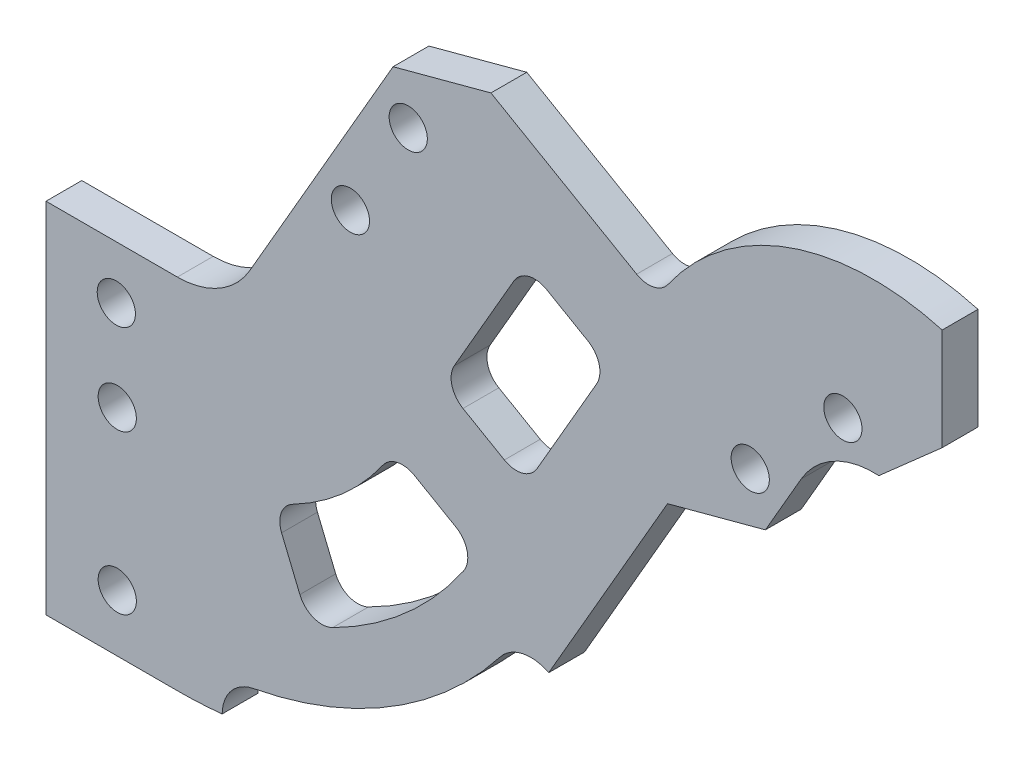
SolidWorks part; units mm, degrees
ref_plane "Front Plane" through (0, 0, 0) normal (0, 0, 1) x (1, 0, 0)
ref_plane "Top Plane" through (0, 0, 0) normal (0, 1, 0) x (1, 0, 0)
ref_plane "Right Plane" through (0, 0, 0) normal (1, 0, 0) x (0, 0, -1)
sketch "Sketch1" plane through (0, 0, 0) normal (0, 0, 1) x (1, 0, 0)
  line L0 (-45.5248, 28.6646) -> (-37.3286, 30.8608) construction
  line L1 (-53.0248, 15.6742) -> (-45.5248, 28.6646) construction
  line L2 (-45.5248, 28.6646) -> (-37.3286, 30.8608)
  line L3 (-57.5248, 7.88) -> (-45.5248, 28.6646)
  line L4 (-30.6183, -5.5166) -> (-22.544, 8.4685) construction
  line L5 (-22.544, 8.4685) -> (-14.3479, 10.6646) construction
  line L6 (-14.3479, 10.6646) -> (-11.3479, 15.8608) construction
  line L7 (-4.8483, 19.3471) -> (0.4544, 24.0249) construction
  line L8 (-32.4942, -8.7657) -> (-22.544, 8.4685)
  line L9 (-22.544, 8.4685) -> (-14.3479, 10.6646)
  line L10 (-14.3479, 10.6646) -> (-11.3479, 15.8608)
  line L11 (-4.8483, 19.3471) -> (0.4544, 24.0249)
  line L12 (0.4544, 24.0249) -> (0.4544, 32.5611)
  line L13 (-63.587, 4.38) -> (-74.587, 4.38)
  line L14 (-74.587, 4.38) -> (-74.587, -25.62)
  line L15 (-74.587, -25.62) -> (-63.587, -25.62)
  line L16 (-63.587, -1.62) -> (-63.587, -25.62) construction
  line L17 (-28.6042, 25.8237) -> (-25.1288, 23.8172) construction
  line L18 (-29.2043, 16.9326) -> (-32.6684, 18.9326) construction
  line L19 (-35.4004, 18.2005) -> (-40.4004, 9.5403) construction
  line L20 (-39.6684, 6.8082) -> (-36.2043, 4.8082) construction
  line L21 (-33.4722, 5.5403) -> (-28.4722, 14.2005) construction
  line L22 (-54.8583, -9.8051) -> (-53.3295, -13.5155) construction
  line L23 (-43.7438, -0.0764) -> (-40.2685, -2.0829) construction
  line L24 (-43.7438, -0.0764) -> (-40.2685, -2.0829)
  line L25 (-54.8583, -9.8051) -> (-53.3295, -13.5155)
  line L26 (-33.4722, 5.5403) -> (-28.4722, 14.2005)
  line L27 (-39.6684, 6.8082) -> (-36.2043, 4.8082)
  line L28 (-35.4004, 18.2005) -> (-40.4004, 9.5403)
  line L29 (-29.2043, 16.9326) -> (-32.6684, 18.9326)
  line L30 (-37.3286, 30.8608) -> (-25.1288, 23.8172)
  arc A2 (-4.8483, 19.3471) -> (-11.3479, 15.8608) centre (-5.2857, 12.3608) ccw construction
  arc A3 (-4.8483, 19.3471) -> (-11.3479, 15.8608) centre (-5.2857, 12.3608) ccw
  arc A4 (-57.5248, 7.88) -> (-63.587, 4.38) centre (-63.587, 11.38) cw
  arc A5 (-57.1936, -22.268) -> (-59.8368, -25.4294) centre (-56.587, -25.4609) ccw
  arc A6 (-32.4942, -8.7657) -> (-36.5568, -9.6541) centre (-33.9919, -11.65) ccw
  arc A7 (-57.1936, -22.268) -> (-36.5568, -9.6541) centre (-63.587, 11.38) ccw
  arc A9 (-63.587, -25.62) -> (-59.8368, -25.4294) centre (-63.587, 11.38) ccw
  arc A10 (-59.7655, -29.4415) -> (-29.1738, -10.9075) centre (-63.587, 11.38) ccw construction
  arc A11 (-63.587, -1.62) -> (-52.3286, 4.88) centre (-63.587, 11.38) ccw construction
  arc A14 (-25.1288, 23.8172) -> (-22.4903, 24.4024) centre (-24.1288, 25.5493) ccw construction
  arc A15 (13.3616, 22.0189) -> (-22.4903, 24.4024) centre (-5.2857, 12.3608) ccw construction
  arc A16 (-32.6684, 18.9326) -> (-35.4004, 18.2005) centre (-33.6684, 17.2005) ccw construction
  arc A17 (-40.4004, 9.5403) -> (-39.6684, 6.8082) centre (-38.6684, 8.5403) ccw construction
  arc A18 (-36.2043, 4.8082) -> (-33.4722, 5.5403) centre (-35.2043, 6.5403) ccw construction
  arc A19 (-28.4722, 14.2005) -> (-29.2043, 16.9326) centre (-30.2043, 15.2005) ccw construction
  arc A20 (-43.7438, -0.0764) -> (-46.3824, -0.6616) centre (-44.7438, -1.8085) ccw construction
  arc A21 (-53.9289, -7.2673) -> (-46.3824, -0.6616) centre (-63.587, 11.38) ccw construction
  arc A22 (-53.9289, -7.2673) -> (-54.8583, -9.8051) centre (-53.0091, -9.0432) ccw construction
  arc A23 (-53.3295, -13.5155) -> (-50.5835, -14.5412) centre (-51.4803, -12.7536) ccw construction
  arc A24 (-50.5835, -14.5412) -> (-39.6153, -4.9405) centre (-63.587, 11.38) ccw construction
  arc A25 (-39.6153, -4.9405) -> (-40.2685, -2.0829) centre (-41.2685, -3.8149) ccw construction
  arc A26 (-50.5835, -14.5412) -> (-39.6153, -4.9405) centre (-63.587, 11.38) ccw
  arc A27 (-53.3295, -13.5155) -> (-50.5835, -14.5412) centre (-51.4803, -12.7536) ccw
  arc A28 (-53.9289, -7.2673) -> (-54.8583, -9.8051) centre (-53.0091, -9.0432) ccw
  arc A29 (-53.9289, -7.2673) -> (-46.3824, -0.6616) centre (-63.587, 11.38) ccw
  arc A30 (-43.7438, -0.0764) -> (-46.3824, -0.6616) centre (-44.7438, -1.8085) ccw
  arc A31 (-28.4722, 14.2005) -> (-29.2043, 16.9326) centre (-30.2043, 15.2005) ccw
  arc A32 (-36.2043, 4.8082) -> (-33.4722, 5.5403) centre (-35.2043, 6.5403) ccw
  arc A33 (-40.4004, 9.5403) -> (-39.6684, 6.8082) centre (-38.6684, 8.5403) ccw
  arc A34 (-32.6684, 18.9326) -> (-35.4004, 18.2005) centre (-33.6684, 17.2005) ccw
  arc A35 (0.4544, 32.5611) -> (-22.4903, 24.4024) centre (-5.2857, 12.3608) ccw
  arc A36 (-25.1288, 23.8172) -> (-22.4903, 24.4024) centre (-24.1288, 25.5493) ccw
  arc A39 (-39.6153, -4.9405) -> (-40.2685, -2.0829) centre (-41.2685, -3.8149) ccw
  circle A40 centre (-7.8608, 22.0235) radius 1.6 construction
  circle A41 centre (-15.6175, 14.4655) radius 1.6 construction
  circle A42 centre (-44.2552, 24.8637) radius 1.6 construction
  circle A43 centre (-49.0983, 16.4751) radius 1.6 construction
  circle A44 centre (-7.8608, 22.0235) radius 1.6
  circle A45 centre (-15.6175, 14.4655) radius 1.6
  circle A46 centre (-44.2552, 24.8637) radius 1.6
  circle A47 centre (-49.0983, 16.4751) radius 1.6
  dimension "D1" = 6.5
  dimension "D2" = 11
extrude "Extrude1" add sketch "Sketch1" along normal blind 3
sketch "Sketch2" plane through (0, 0, 0) normal (0, 0, -1) x (-1, 0, 0)
  circle A0 centre (68.7008, -0.06) radius 1.6
  circle A1 centre (68.6208, -7.5918) radius 1.6
  circle A2 centre (68.6208, -20.852) radius 1.6
  dimension "D1" = 3.2
extrude "Cut-Extrude1" cut sketch "Sketch2" against normal blind 10
